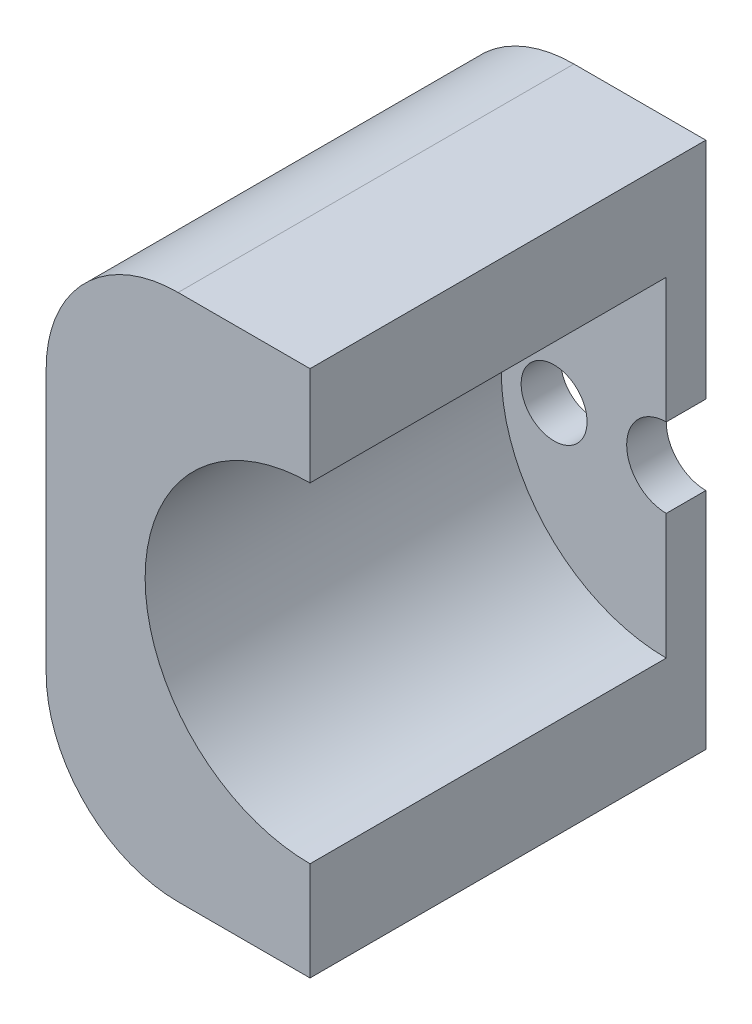
SolidWorks part; units mm, degrees
ref_plane "Front Plane" through (0, 0, 0) normal (0, 0, 1) x (1, 0, 0)
ref_plane "Top Plane" through (0, 0, 0) normal (0, 1, 0) x (1, 0, 0)
ref_plane "Right Plane" through (0, 0, 0) normal (1, 0, 0) x (0, 0, -1)
sketch "Sketch1" plane through (0, 0, 0) normal (0, 0, 1) x (1, 0, 0)
  line L0 (0, 20) -> (0, -20) construction
  line L1 (-20, 20) -> (0, 20)
  line L2 (-20, 20) -> (-20, -20)
  line L3 (-20, -20) -> (0, -20)
  line L5 (-20, 20) -> (0, 0) construction
  line L6 (-20, -20) -> (0, 0) construction
  line L7 (0, 20) -> (0, 12.5)
  line L8 (0, -20) -> (0, -12.5)
  arc A0 (0, 12.5) -> (0, -12.5) centre (0, 0) ccw
  point P1 (-20, 0)
  dimension "D1" = 25
  dimension "D2" = 20
  dimension "D3" = 40
extrude "Boss-Extrude1" add sketch "Sketch1" along normal blind 30
sketch "Sketch2" plane through (0, 0, 0) normal (0, 0, -1) x (-1, 0, 0)
  line L0 (0, -12.5) -> (0, -3)
  line L1 (0, 3) -> (0, 12.5)
  arc A0 (0, -12.5) -> (0, 12.5) centre (0, 0) ccw construction
  arc A1 (0, -12.5) -> (0, 12.5) centre (0, 0) ccw
  arc A2 (0, -3) -> (0, 3) centre (0, 0) ccw
  circle A3 centre (8.5, 0) radius 2.5
  dimension "D1" = 6
  dimension "D2" = 5
extrude "Boss-Extrude2" add sketch "Sketch2" against normal blind 3
fillet "Fillet1" radius 10 2 edges at (-20, -20, 15) (-20, 20, 15)
